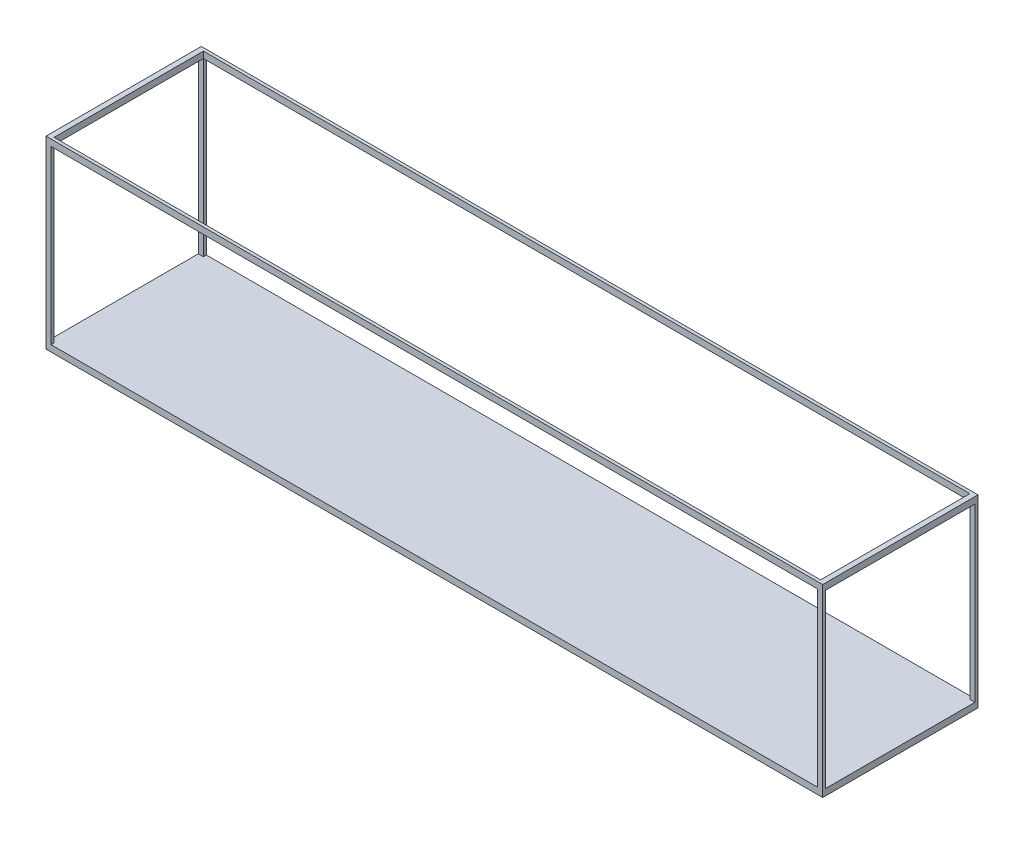
SolidWorks part; units mm, degrees
ref_plane "Front Plane" through (0, 0, 0) normal (0, 0, 1) x (1, 0, 0)
ref_plane "Top Plane" through (0, 0, 0) normal (0, 1, 0) x (1, 0, 0)
ref_plane "Right Plane" through (0, 0, 0) normal (1, 0, 0) x (0, 0, -1)
sketch "Sketch1" plane through (0, 0, 0) normal (0, 0, 1) x (1, 0, 0)
  line L1 (-5.3134, 2696.8133) -> (12026.6866, 2696.8133)
  line L2 (-5.3134, 2696.8133) -> (-5.3134, 1.8133)
  line L3 (-5.3134, 1.8133) -> (12026.6866, 1.8133)
  line L4 (12026.6866, 2696.8133) -> (12026.6866, 1.8133)
  line L16 (12106.6866, 2797.3133) -> (-85.3134, 2797.3133)
  line L17 (12106.6866, 2797.3133) -> (12106.6866, -98.6867)
  line L18 (12106.6866, -98.6867) -> (-85.3134, -98.6867)
  line L19 (-85.3134, 2797.3133) -> (-85.3134, -98.6867)
  dimension "D1" = 12032
  dimension "D2" = 2695
  dimension "D3" = 80
  dimension "D4" = 12192
  dimension "D5" = 100.5
  dimension "D6" = 2896
extrude "Boss-Extrude1" add sketch "Sketch1" along normal blind 2438
sketch "Sketch4" plane through (0, 1.8133, 0) normal (0, 1, 0) x (1, 0, 0)
  line L1 (208.7638, -2250) -> (4208.7638, -2250)
  line L2 (208.7638, -2250) -> (208.7638, -750)
  line L3 (208.7638, -750) -> (4208.7638, -750)
  line L4 (4208.7638, -2250) -> (4208.7638, -750)
  line L5 (-5.3134, -2438) -> (-5.3134, 0) construction
  line L11 (2294.6866, -646.2771) -> (2854.6866, -646.2771)
  line L12 (2294.6866, -646.2771) -> (2294.6866, -86.2771)
  line L13 (2294.6866, -86.2771) -> (2854.6866, -86.2771)
  line L14 (2854.6866, -646.2771) -> (2854.6866, -86.2771)
  line L19 (6755.0444, -530) -> (10405.0444, -530)
  line L20 (6755.0444, -530) -> (6755.0444, -2250)
  line L21 (6755.0444, -2250) -> (10405.0444, -2250)
  line L22 (10405.0444, -530) -> (10405.0444, -2250)
  line L24 (3004.6866, -120) -> (6504.6866, -120)
  line L25 (3004.6866, -120) -> (3004.6866, -600)
  line L26 (3004.6866, -600) -> (6504.6866, -600)
  line L27 (6504.6866, -120) -> (6504.6866, -600)
  line L28 (4360.7767, -930) -> (6462.7767, -930)
  line L29 (4360.7767, -930) -> (4360.7767, -2250)
  line L30 (4360.7767, -2250) -> (6462.7767, -2250)
  line L31 (6462.7767, -930) -> (6462.7767, -2250)
  line L32 (10584.3406, -80) -> (11884.3406, -80)
  line L33 (10584.3406, -80) -> (10584.3406, -2180)
  line L34 (10584.3406, -2180) -> (11884.3406, -2180)
  line L35 (11884.3406, -80) -> (11884.3406, -2180)
  line L37 (6755.0444, -120) -> (10405.0444, -120)
  line L38 (6755.0444, -120) -> (6755.0444, -420)
  line L39 (6755.0444, -420) -> (10405.0444, -420)
  line L40 (10405.0444, -120) -> (10405.0444, -420)
  point P28 (6504.6866, -360)
  dimension "D5" = 560
  dimension "D1" = 1500
  dimension "D2" = 4000
  dimension "D3" = 150
  dimension "D6" = 560
  dimension "D7" = 2300
  dimension "D8" = 2102
  dimension "D9" = 3650
  dimension "D10" = 1720
  dimension "D11" = 1320
  dimension "D12" = 1300
  dimension "D13" = 2100
  dimension "D14" = 3500
  dimension "D15" = 240
  dimension "D16" = 150
  dimension "D17" = 3650
  dimension "D18" = 300
sketch "Sketch5" plane through (0, 2797.3133, 0) normal (0, 1, 0) x (1, 0, 0)
  line L9 (-85.3134, -2438) -> (-85.3134, 0) construction
  line L10 (12026.6866, -2391) -> (-5.3134, -2391)
  line L11 (12026.6866, -2391) -> (12026.6866, -47)
  line L12 (12026.6866, -47) -> (-5.3134, -47)
  line L13 (-5.3134, -2391) -> (-5.3134, -47)
  line L14 (12106.6866, -2438) -> (12106.6866, 0) construction
  line L15 (12106.6866, -2438) -> (-85.3134, -2438) construction
  line L16 (12106.6866, 0) -> (-85.3134, 0) construction
  dimension "D1" = 80
  dimension "D2" = 80
  dimension "D3" = 47
  dimension "D4" = 47
extrude "Cut-Extrude2" cut sketch "Sketch5" against normal blind 100.5
sketch "Sketch6" plane through (12106.6866, 0, 0) normal (1, 0, 0) x (0, 0, -1)
  line L0 (-2438, -98.6867) -> (-2438, 2797.3133) construction
  line L1 (-2391, 2696.8133) -> (-47, 2696.8133)
  line L2 (-2391, 2696.8133) -> (-2391, 1.8133)
  line L3 (-2391, 1.8133) -> (-47, 1.8133)
  line L4 (-47, 2696.8133) -> (-47, 1.8133)
  line L8 (-2438, -98.6867) -> (0, -98.6867) construction
  dimension "D1" = 2344
  dimension "D2" = 47
  dimension "D3" = 100.5
extrude "Cut-Extrude5" cut sketch "Sketch6" against normal through all
